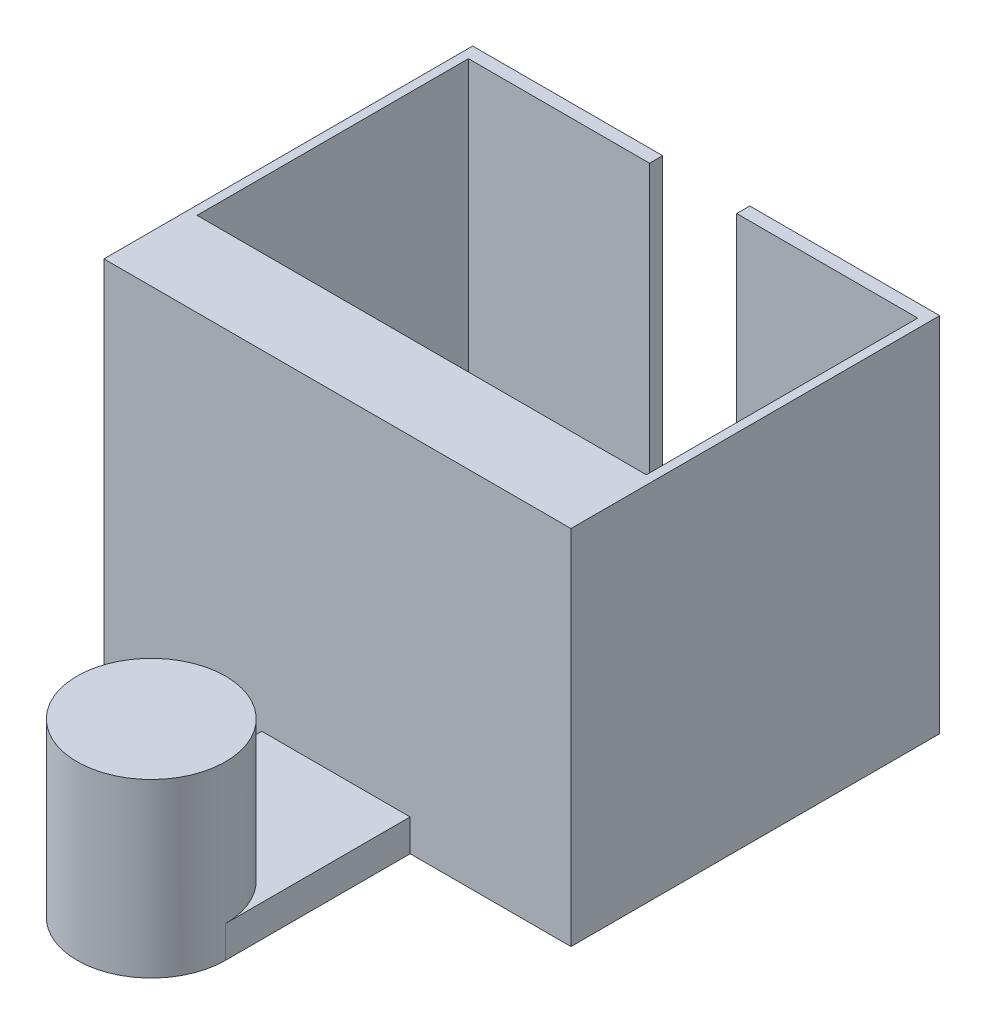
SolidWorks part; units mm, degrees
ref_plane "Front Plane" through (0, 0, 0) normal (0, 0, 1) x (1, 0, 0)
ref_plane "Top Plane" through (0, 0, 0) normal (0, 1, 0) x (1, 0, 0)
ref_plane "Right Plane" through (0, 0, 0) normal (1, 0, 0) x (0, 0, -1)
sketch "Sketch2" plane through (0, 0, 0) normal (0, 1, 0) x (1, 0, 0)
  line L0 (66.6966, 107.7866) -> (66.6966, 105.9529)
  line L1 (40.0418, 56.0489) -> (105.5738, 56.0489)
  line L2 (40.0418, 56.0489) -> (40.0418, 107.7866)
  line L3 (40.0418, 107.7866) -> (66.6966, 107.7866)
  line L4 (105.5738, 56.0489) -> (105.5738, 107.7866)
  line L5 (66.6966, 105.9529) -> (41.2864, 105.9529)
  line L6 (41.2864, 105.9529) -> (41.2864, 67.872)
  line L7 (41.2864, 67.872) -> (104.3292, 67.872)
  line L8 (104.3292, 67.872) -> (104.3292, 105.9529)
  line L9 (104.3292, 105.9529) -> (78.9191, 105.9529)
  line L10 (78.9191, 105.9529) -> (78.9191, 107.7866)
  line L11 (78.9191, 107.7866) -> (105.5738, 107.7866)
  dimension "D1" = 25.4102
  dimension "D2" = 63.0428
  dimension "D3" = 1.8337
  dimension "D4" = 38.0809
  dimension "D5" = 11.8231
  dimension "D6" = 65.532
extrude "Boss-Extrude1" add sketch "Sketch2" along normal blind 50.8
sketch "Sketch3" plane through (0, 0, -56.0489) normal (0, 0, 1) x (1, 0, 0)
  line L1 (62.1781, 0) -> (83.0108, 0)
  line L2 (62.1781, 0) -> (62.1781, 4.4733)
  line L3 (62.1781, 4.4733) -> (83.0108, 4.4733)
  line L4 (83.0108, 0) -> (83.0108, 4.4733)
  point P4 (0, 0)
  point P5 (0, 0)
  point P10 (0, 0)
  point P11 (0, 0)
  point P12 (0, 0)
  point P13 (0, 0)
  dimension "D1" = 20.8326
  dimension "D2" = 4.4733
extrude "Boss-Extrude2" add sketch "Sketch3" along normal blind 25.908
sketch "Sketch5" plane through (0, 0, 0) normal (0, -1, 0) x (1, 0, 0)
  line L0 (62.1781, -30.1409) -> (83.0108, -30.1409) construction
  circle A0 centre (72.5945, -30.1409) radius 10.4163
  dimension "D1" = 20.8326
extrude "Boss-Extrude3" add sketch "Sketch5" against normal blind 24.13
equation "\"SF\"= 4'Safety Factor"
equation "\"Yeild Strength\"= 36000"
equation "\"6_a\"= \"Yeild Strength\" / \"SF\""
equation "\"W\" = 1300'Load"
equation "\"L\" = 0.75'L_min"
equation "\"Z\"= \"W\" * \"L\" / \"6_a\"'Z_min"
equation "\"D_1\"= ( ( 16 / pi ) * \"Z\" ) ^ ( 1 / 3 )"
equation "\"D1@Sketch5\"=\"D_1\""
equation "\"A_2\"= \"W\" / \"6_a\""
equation "\"Depth\" = \"D_1\""
equation "\"Width_2\"= \"A_2\" / \"Depth\""
equation "\"D1@Sketch3\"=\"D_1\""
equation "\"D2@Sketch3\"=\"Width_2\""
equation "\"L_3\"= 2.482'By Geometry"
equation "\"Z_3\"= \"W\" * \"L_3\" / ( 4 * \"6_a\" )"
equation "\"H_3\"= ( \"Z_3\" * 6 / \"L_3\" ) ^ ( 1 / 2 )"
equation "\"D5@Sketch2\"=\"H_3\""
equation "\"A_4\"= ( \"W\" / 2 ) / \"6_a\"'A_min"
equation "\"C_m\"= 1.498"
equation "\"W_4\"= \"A_4\" / \"C_m\""
equation "\"C_4\"= 1.49925'C with tol"
equation "\"B_5\"= 1.0004'B with tol"
equation "\"A_5\"= .5008'A with tol"
equation "\"H_5\"= \"A_4\" / \"B_5\""
equation "\"D3@Sketch2\"=\"H_5\""
equation "\"D1@Sketch2\"=\"B_5\""
equation "\"D4@Sketch2\"=\"C_4\""
